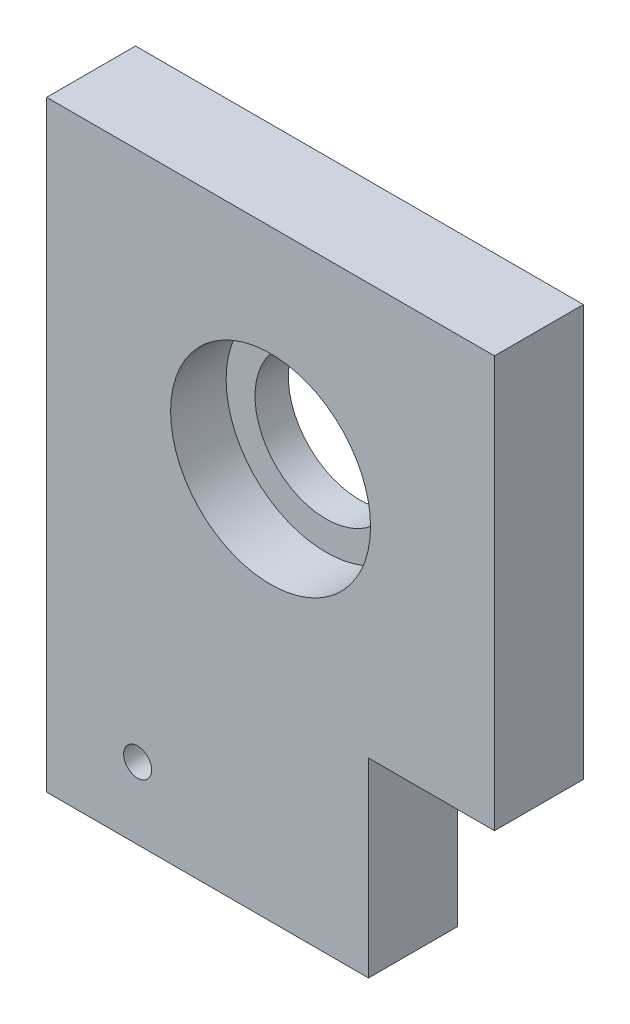
SolidWorks part; units mm, degrees
material "Plain Carbon Steel"
ref_plane "Front Plane" through (0, 0, 0) normal (0, 0, 1) x (1, 0, 0)
ref_plane "Top Plane" through (0, 0, 0) normal (0, 1, 0) x (1, 0, 0)
ref_plane "Right Plane" through (0, 0, 0) normal (1, 0, 0) x (0, 0, -1)
sketch "Sketch1" plane through (0, 0, 0) normal (0, 0, 1) x (1, 0, 0)
  line L1 (14, -56) -> (-32, -56)
  line L2 (-32, -56) -> (-32, 0)
  line L3 (0, 0) -> (0, -56) construction
  line L4 (-32, 0) -> (32, 0) construction
  line L5 (14, -56) -> (14, -28.775)
  line L6 (14, -28.775) -> (32, -28.775)
  line L7 (32, -28.775) -> (32, 30)
  line L8 (32, 30) -> (-32, 30)
  line L9 (-32, 30) -> (-32, 0)
  circle A0 centre (0, 0) radius 14.2875 construction
  circle A4 centre (0, 0) radius 10.16
  circle A5 centre (-19, -45.775) radius 2
  dimension "D1" = 32
  dimension "D2" = 46
  dimension "D6" = 20.32
  dimension "D7" = 4
  dimension "D3" = 56
  dimension "D4" = 30
  dimension "D5" = 27.225
  dimension "D8" = 13
  dimension "D9" = 17
extrude "Boss-Extrude1" add sketch "Sketch1" along normal blind 12.7
sketch "Sketch2" plane through (0, 0, 0) normal (0, 0, 1) x (1, 0, 0)
  circle A0 centre (0, 0) radius 14.2875
  dimension "D1" = 28.575
extrude "Cut-Extrude1" cut sketch "Sketch2" against normal blind 7.9375 from surface at 12.7 starting at face at (10.16, 0, 12.7)
